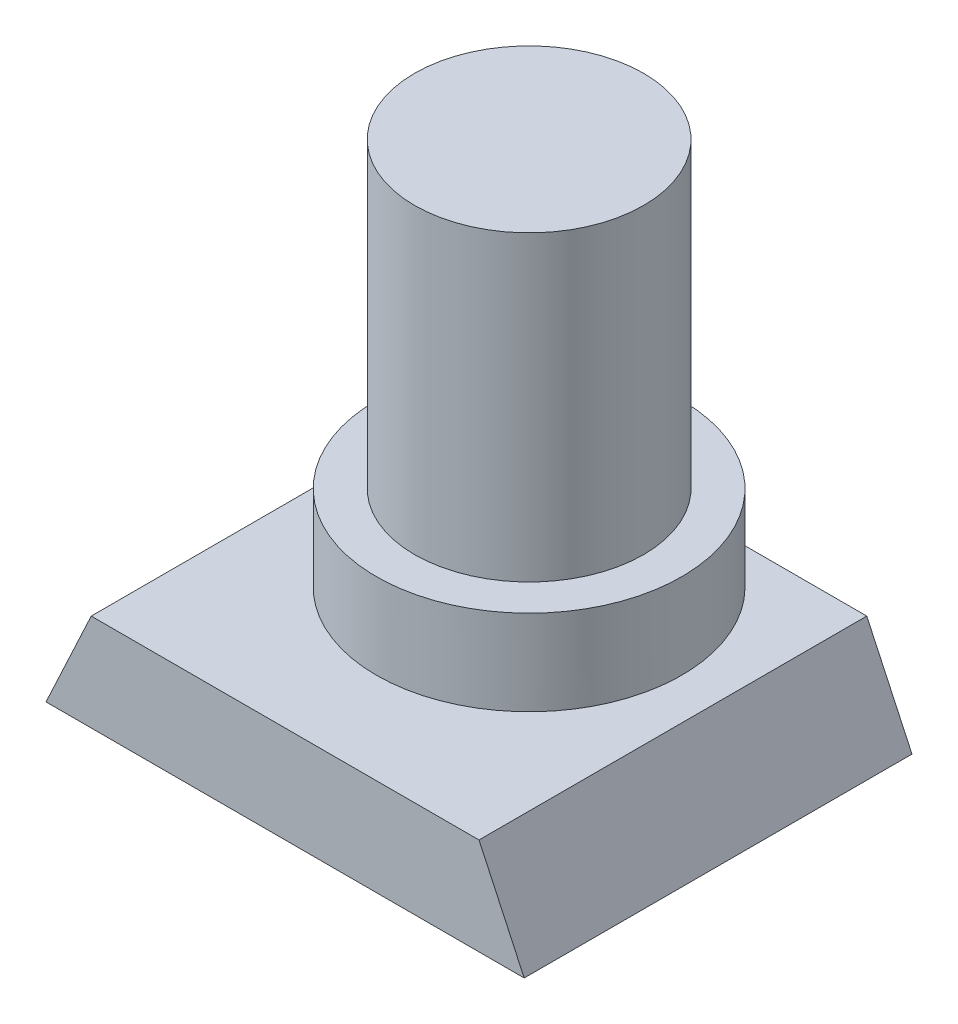
SolidWorks part; units mm, degrees
ref_plane "Front Plane" through (0, 0, 0) normal (0, 0, 1) x (1, 0, 0)
ref_plane "Top Plane" through (0, 0, 0) normal (0, 1, 0) x (1, 0, 0)
ref_plane "Right Plane" through (0, 0, 0) normal (1, 0, 0) x (0, 0, -1)
sketch "Sketch1" plane through (0, 0, 0) normal (0, 0, 1) x (1, 0, 0)
  line L0 (-7.8305, 0) -> (7.8305, 0)
  line L1 (7.8305, 0) -> (6.35, 3.175)
  line L2 (6.35, 3.175) -> (-6.35, 3.175)
  line L3 (-6.35, 3.175) -> (-7.8305, 0)
  dimension "D1" = 3.175
  dimension "D2" = 12.7
  dimension "D3" = 65
extrude "Boss-Extrude1" add sketch "Sketch1" along normal blind 12.7
sketch "Sketch2" plane through (0, 3.175, 0) normal (0, 1, 0) x (1, 0, 0)
  line L0 (0, 0) -> (0, -4.7088) construction
  circle A0 centre (0, -4.7088) radius 3.75
  dimension "D1" = 7.5
extrude "Boss-Extrude2" add sketch "Sketch2" along normal blind 12.7
sketch "Sketch3" plane through (0, 3.175, 0) normal (0, 1, 0) x (1, 0, 0)
  circle A0 centre (0, -4.7088) radius 5
  dimension "D1" = 10
extrude "Boss-Extrude3" add sketch "Sketch3" along normal offset from surface (2.796 mm away) 0.254
